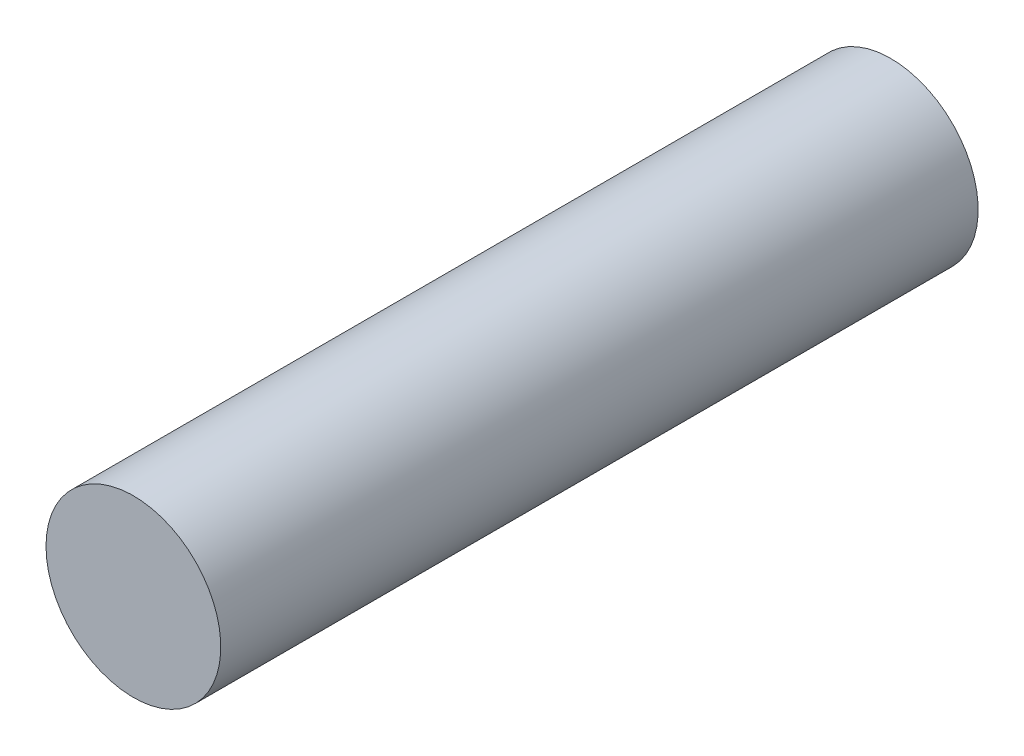
SolidWorks part; units mm, degrees
ref_plane "Front Plane" through (0, 0, 0) normal (0, 0, 1) x (1, 0, 0)
ref_plane "Top Plane" through (0, 0, 0) normal (0, 1, 0) x (1, 0, 0)
ref_plane "Right Plane" through (0, 0, 0) normal (1, 0, 0) x (0, 0, -1)
sketch "Sketch1" plane through (0, 0, 0) normal (0, 0, 1) x (1, 0, 0)
  circle A0 centre (0, 0) radius 19.05
  dimension "D1" = 38.1
extrude "Boss-Extrude1" add sketch "Sketch1" along normal blind 165.1
